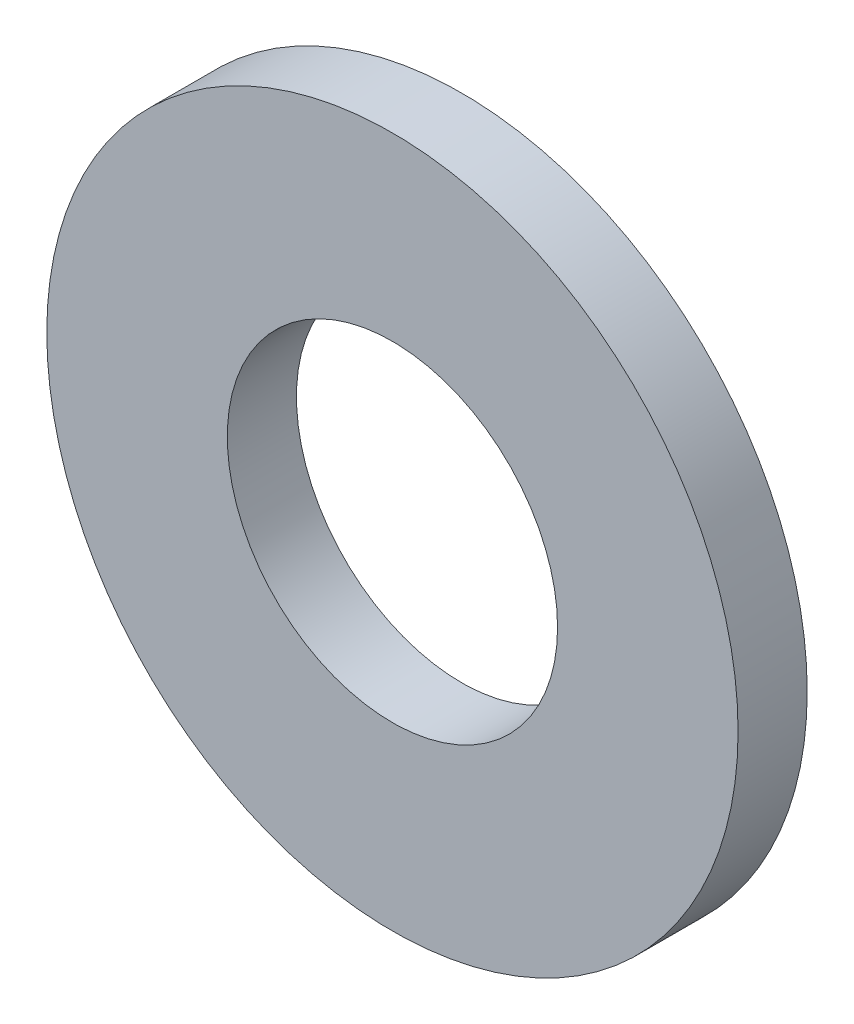
SolidWorks part; units mm, degrees
ref_plane "前视基准面" through (0, 0, 0) normal (0, 0, 1) x (1, 0, 0)
ref_plane "上视基准面" through (0, 0, 0) normal (0, 1, 0) x (1, 0, 0)
ref_plane "右视基准面" through (0, 0, 0) normal (1, 0, 0) x (0, 0, -1)
sketch "草图1" plane through (0, 0, 0) normal (0, 0, 1) x (1, 0, 0)
  circle A0 centre (0, 0) radius 2.15
  circle A1 centre (0, 0) radius 4.5
  dimension "D1" = 4.3
  dimension "D2" = 9
extrude "凸台-拉伸1" add sketch "草图1" along normal blind 0.9
